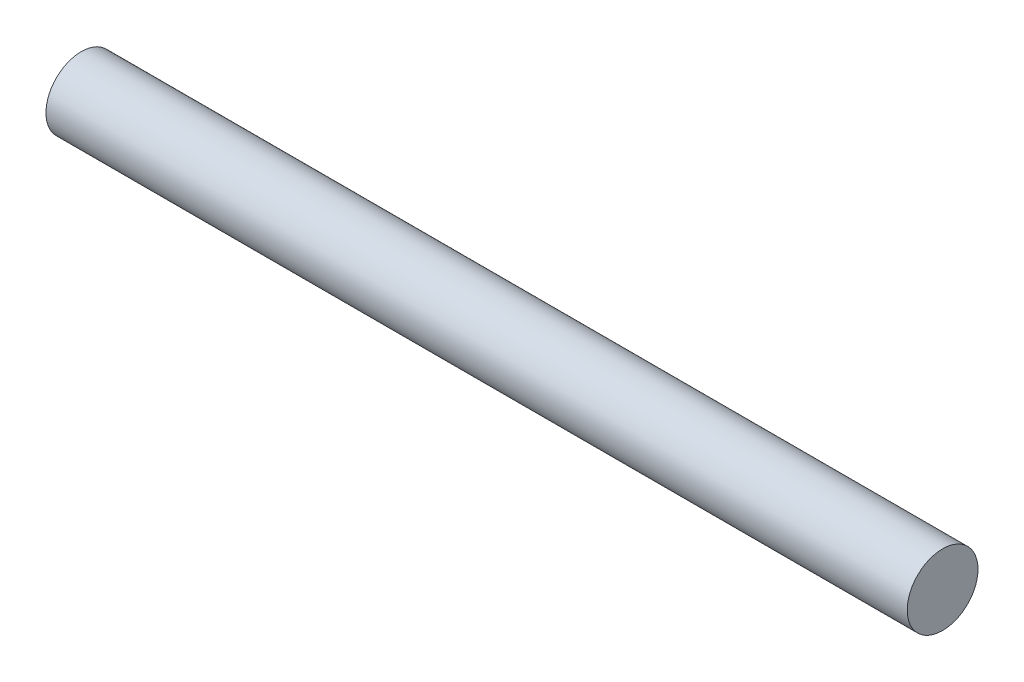
SolidWorks part; units mm, degrees
material "Stainless Steel (ferritic)"
ref_plane "Front Plane" through (0, 0, 0) normal (0, 0, 1) x (1, 0, 0)
ref_plane "Top Plane" through (0, 0, 0) normal (0, 1, 0) x (1, 0, 0)
ref_plane "Right Plane" through (0, 0, 0) normal (1, 0, 0) x (0, 0, -1)
sketch "Sketch2" plane through (0, 0, 0) normal (1, 0, 0) x (0, 0, -1)
  circle A0 centre (0, 0) radius 1.5
  dimension "D1" = 3
extrude "Boss-Extrude1" add sketch "Sketch2" along normal blind 36.5
